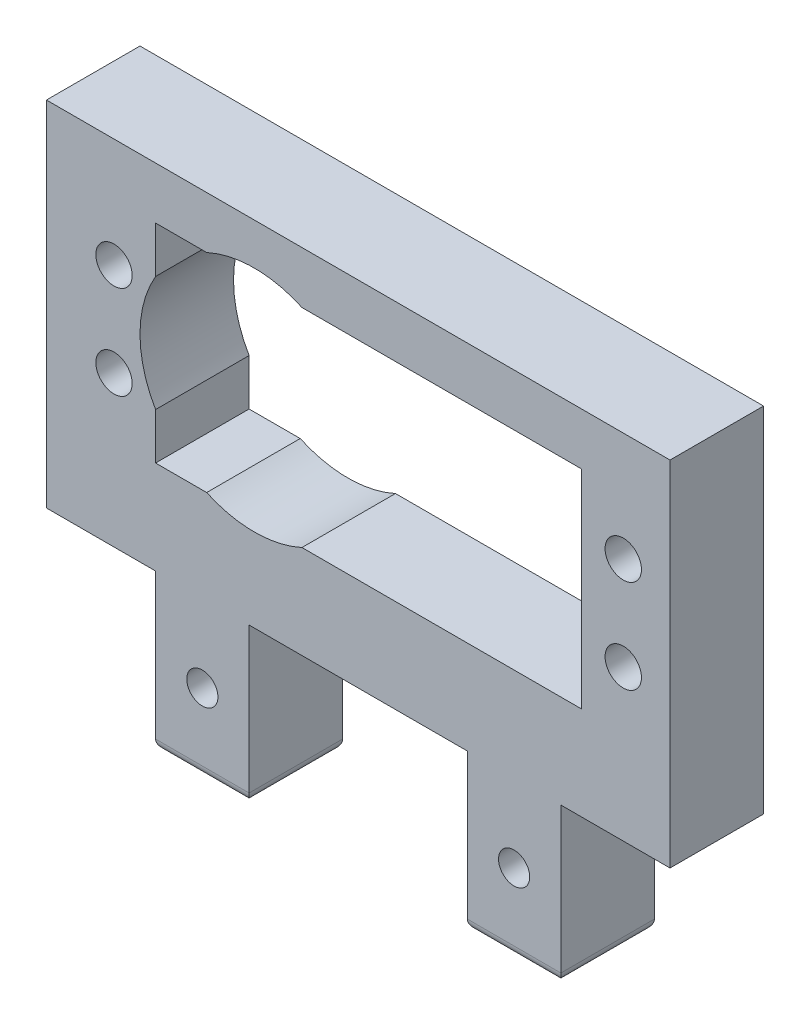
SolidWorks part; units mm, degrees
ref_plane "Alzado" through (0, 0, 0) normal (0, 0, 1) x (1, 0, 0)
ref_plane "Planta" through (0, 0, 0) normal (0, 1, 0) x (1, 0, 0)
ref_plane "Vista lateral" through (0, 0, 0) normal (1, 0, 0) x (0, 0, -1)
sketch "Croquis1" plane through (0, 0, 0) normal (0, 0, 1) x (1, 0, 0)
  line L0 (10.5, -15) -> (49.5, -15) construction
  line L1 (0, 0) -> (60, 0)
  line L2 (0, 0) -> (0, 34)
  line L3 (0, 34) -> (60, 34)
  line L4 (60, 0) -> (60, 34)
  line L5 (10.5, -7.5) -> (49.5, -7.5) construction
  line L6 (10.5, -15) -> (19.5, -15)
  line L7 (10.5, -15) -> (10.5, 0)
  line L8 (10.5, 0) -> (19.5, 0)
  line L9 (19.5, -15) -> (19.5, 0)
  line L10 (49.5, -15) -> (40.5, -15)
  line L11 (49.5, -15) -> (49.5, 0)
  line L12 (49.5, 0) -> (40.5, 0)
  line L13 (40.5, -15) -> (40.5, 0)
  line L14 (10.5, 29) -> (51.5, 29)
  line L15 (10.5, 29) -> (10.5, 9)
  line L16 (10.5, 9) -> (51.5, 9)
  line L17 (51.5, 29) -> (51.5, 9)
  line L18 (15, -15) -> (15, 0) construction
  line L19 (45, -15) -> (45, 0) construction
  line L20 (55.5, 33.4132) -> (55.5, -4.9176) construction
  line L21 (6.5, 38.3733) -> (6.5, 0.0424) construction
  line L22 (6.5, 19) -> (55.5, 19) construction
  line L23 (6.5, 23.5) -> (55.5, 23.5) construction
  line L24 (6.5, 14.5) -> (55.5, 14.5) construction
  circle A0 centre (6.5, 23.5) radius 1.75
  circle A1 centre (6.5, 14.5) radius 1.75
  circle A2 centre (55.5, 23.5) radius 1.75
  circle A3 centre (55.5, 14.5) radius 1.75
  circle A4 centre (15, -7.5) radius 1.5
  circle A5 centre (45, -7.5) radius 1.5
  circle A6 centre (20, 19) radius 11
  point P37 (20, 19)
  point P44 (0, 0)
  dimension "D14" = 3.5
  dimension "D15" = 3.5
  dimension "D16" = 3.5
  dimension "D17" = 3.5
  dimension "D21" = 3
  dimension "D22" = 3
  dimension "D23" = 22
  dimension "D1" = 15
  dimension "D2" = 10.5
  dimension "D3" = 9
  dimension "D4" = 10.5
  dimension "D5" = 9
  dimension "D6" = 60
  dimension "D7" = 41
  dimension "D8" = 4
  dimension "D9" = 4
  dimension "D10" = 20
  dimension "D11" = 10
  dimension "D12" = 4.5
  dimension "D13" = 4.5
  dimension "D18" = 9.5
  dimension "D19" = 19
  dimension "D20" = 5
  dimension "D24" = 20
extrude "Saliente-Extruir1" add sketch "Croquis1" along normal blind 9 contours L1 L4 L3 L2 A6 L14 L17 L16 L15 A3 A2 A1 A0 | L6 L9 L1 L7 A4 | L13 L10 L11 L1 A5
fillet "Redondeo1" radius 1 8 edges at (40.5, -15, 4.5) (45, -15, 9) (49.5, -15, 4.5) (45, -15, 0) (10.5, -15, 4.5) (15, -15, 9) (19.5, -15, 4.5) (15, -15, 0)
